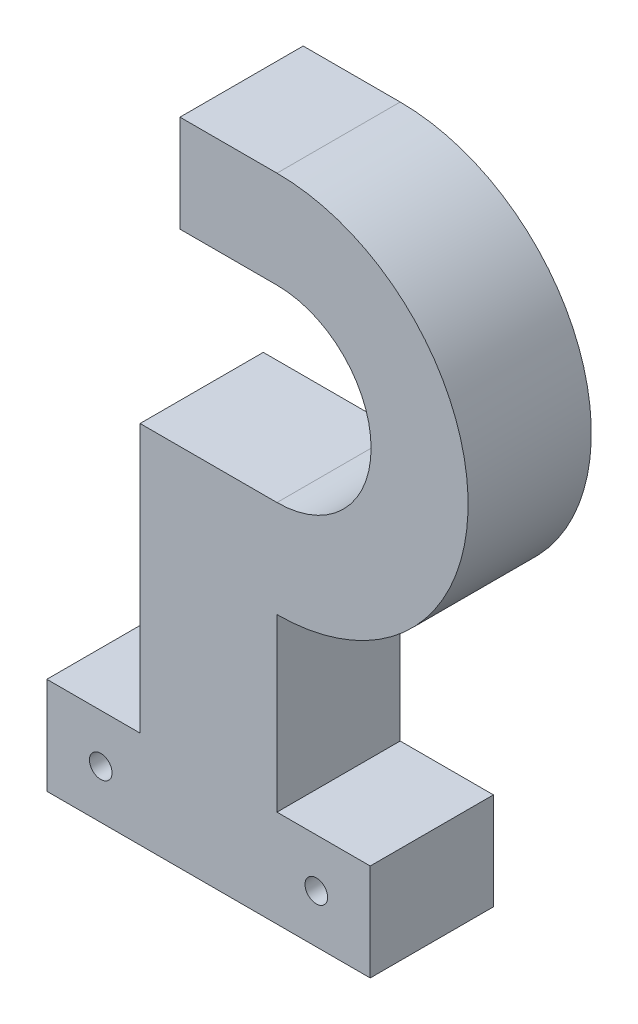
SolidWorks part; units mm, degrees
ref_plane "Front Plane" through (0, 0, 0) normal (0, 0, 1) x (1, 0, 0)
ref_plane "Top Plane" through (0, 0, 0) normal (0, 1, 0) x (1, 0, 0)
ref_plane "Right Plane" through (0, 0, 0) normal (1, 0, 0) x (0, 0, -1)
other "Graphic1"
other "Graphic (Closed) -1"
ref_plane "Plane1" through (0, 0, -6.35) normal (0, 0, 1) x (1, 0, 0)
sketch "Sketch3" plane through (0, 0, -6.35) normal (0, 0, 1) x (1, 0, 0)
  line L0 (-2.6638, 22.925) -> (-20.6638, 22.925)
  line L1 (-20.6638, 22.925) -> (-20.6638, 4.925)
  line L2 (-20.6638, 4.925) -> (-2.6638, 4.925)
  line L3 (-2.6638, -30) -> (-28.0638, -30)
  line L4 (-28.0638, -30) -> (-28.0638, -48)
  line L5 (-28.0638, -48) -> (-2.6638, -48)
  arc A2 (-2.6638, -30) -> (-2.6638, 4.925) centre (-2.6638, -12.5375) ccw
  arc A3 (-2.6638, -48) -> (-2.6638, 22.925) centre (-2.6638, -12.5375) ccw
  dimension "D1" = 0
extrude "Boss-Extrude1" add sketch "Sketch3" against normal blind 22.86 contours L5 A3 L0 L1 L2 A2 L3 L4
sketch "Sketch4" plane through (0, -48, 0) normal (0, -1, 0) x (1, 0, 0)
  line L1 (-28.0638, -6.35) -> (-2.6638, -6.35)
  line L2 (-28.0638, -6.35) -> (-28.0638, -29.21)
  line L3 (-28.0638, -29.21) -> (-2.6638, -29.21)
  line L4 (-2.6638, -6.35) -> (-2.6638, -29.21)
extrude "Boss-Extrude2" add sketch "Sketch4" along normal blind 31.75
sketch "Sketch5" plane through (0, 0, -6.35) normal (0, 0, 1) x (1, 0, 0)
  line L0 (-15.3638, -79.75) -> (14.6362, -79.75)
  line L1 (-2.6638, -79.75) -> (-28.0638, -79.75) construction
  line L2 (-15.3638, -79.75) -> (-45.3638, -79.75)
  line L3 (-45.3638, -79.75) -> (-45.3638, -97.75)
  line L4 (-45.3638, -97.75) -> (14.6362, -97.75)
  line L5 (14.6362, -97.75) -> (14.6362, -79.75)
  dimension "D1" = 18
extrude "Boss-Extrude3" add sketch "Sketch5" against normal blind 22.86 contours L4 L5 L0 L2 L3
sketch "Sketch6" plane through (0, 0, -6.35) normal (0, 0, 1) x (1, 0, 0)
  line L0 (14.6362, -88.75) -> (4.6362, -88.75)
  line L1 (14.6362, -97.75) -> (14.6362, -79.75) construction
  line L2 (-45.3638, -88.75) -> (-35.3638, -88.75)
  line L3 (-45.3638, -79.75) -> (-45.3638, -97.75) construction
  circle A0 centre (-35.3638, -88.75) radius 2.1
  circle A1 centre (4.6362, -88.75) radius 2.1
extrude "Cut-Extrude1" cut sketch "Sketch6" against normal blind 22.86
